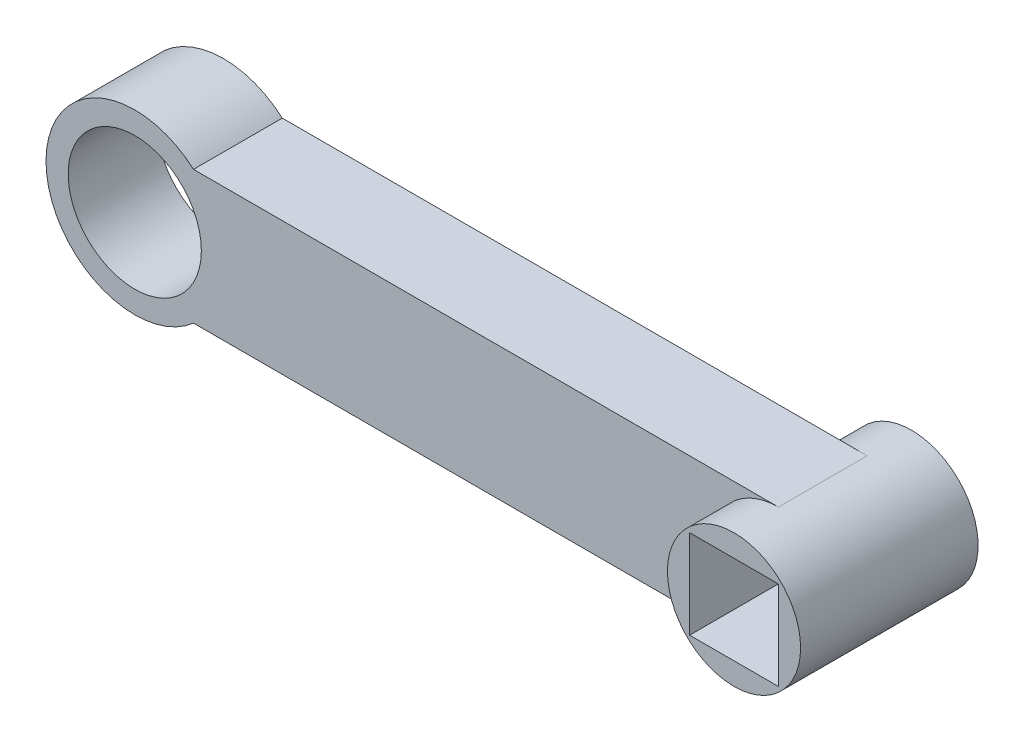
SolidWorks part; units mm, degrees
ref_plane "Front Plane" through (0, 0, 0) normal (0, 0, 1) x (1, 0, 0)
ref_plane "Top Plane" through (0, 0, 0) normal (0, 1, 0) x (1, 0, 0)
ref_plane "Right Plane" through (0, 0, 0) normal (1, 0, 0) x (0, 0, -1)
sketch "Sketch1" plane through (0, 0, 0) normal (0, 0, 1) x (1, 0, 0)
  line L1 (72.5, -15) -> (-59.2712, -15)
  line L3 (72.5, 15) -> (-59.2712, 15)
  arc A0 (-59.2712, 15) -> (-59.2712, -15) centre (-72.5, 0) ccw
  circle A1 centre (-72.5, 0) radius 15
  arc A2 (72.5, -15) -> (72.5, 15) centre (72.5, 0) ccw
  point P0 (0, 0)
extrude "Boss-Extrude2" add sketch "Sketch1" along normal blind 20
sketch "Sketch3" plane through (0, 0, 20) normal (0, 0, 1) x (1, 0, 0)
  circle A0 centre (72.5, 0) radius 15
extrude "Boss-Extrude3" add sketch "Sketch3" along normal blind 10
sketch "Sketch5" plane through (0, 0, 0) normal (0, 0, -1) x (-1, 0, 0)
  circle A0 centre (-72.5, 0) radius 15
extrude "Boss-Extrude4" add sketch "Sketch5" along normal blind 10
sketch "Sketch6" plane through (0, 0, -10) normal (0, 0, -1) x (-1, 0, 0)
  line L1 (-62.5, -10) -> (-82.5, -10)
  line L2 (-62.5, -10) -> (-62.5, 10)
  line L3 (-62.5, 10) -> (-82.5, 10)
  line L4 (-82.5, -10) -> (-82.5, 10)
  line L5 (-62.5, -10) -> (-82.5, 10) construction
  line L6 (-62.5, 10) -> (-82.5, -10) construction
  point P0 (-72.5, 0)
  dimension "D1" = 20
  dimension "D2" = 20
extrude "Cut-Extrude1" cut sketch "Sketch6" against normal blind 50
sketch "Sketch8" plane through (0, 0, 0) normal (0, 0, -1) x (-1, 0, 0)
  point P0 (-72.5, 0)
